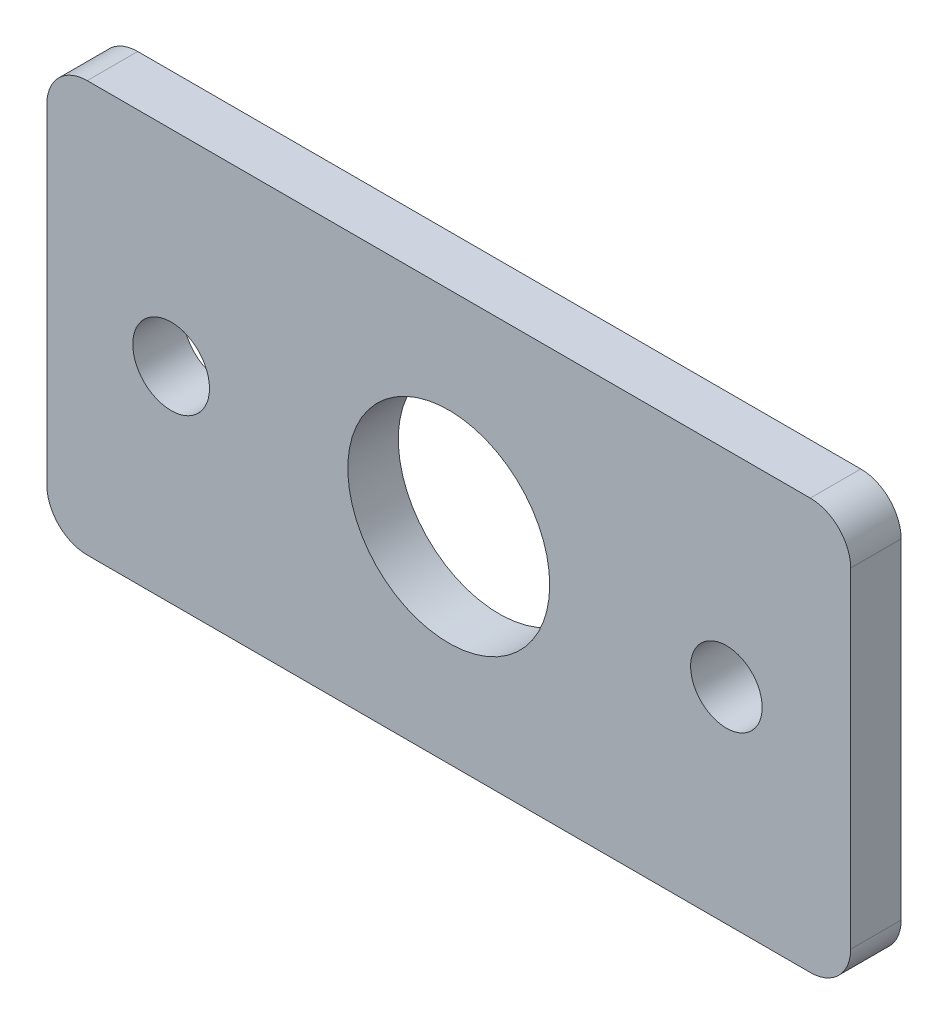
SolidWorks part; units mm, degrees
material "Plain Carbon Steel"
ref_plane "Front Plane" through (0, 0, 0) normal (0, 0, 1) x (1, 0, 0)
ref_plane "Top Plane" through (0, 0, 0) normal (0, 1, 0) x (1, 0, 0)
ref_plane "Right Plane" through (0, 0, 0) normal (1, 0, 0) x (0, 0, -1)
sketch "Sketch1" plane through (0, 0, 0) normal (0, 0, 1) x (1, 0, 0)
  line L1 (-25.2779, -12.9213) -> (25.2779, -12.9213)
  line L2 (-25.2779, -12.9213) -> (-25.2779, 12.9213)
  line L3 (-25.2779, 12.9213) -> (25.2779, 12.9213)
  line L4 (25.2779, -12.9213) -> (25.2779, 12.9213)
  line L5 (-25.2779, -12.9213) -> (25.2779, 12.9213) construction
  line L6 (-25.2779, 12.9213) -> (25.2779, -12.9213) construction
  circle A0 centre (-17.4625, 0) radius 2.413
  circle A1 centre (17.4625, 0) radius 2.2498
  circle A2 centre (0, 0) radius 6.35
extrude "Boss-Extrude1" add sketch "Sketch1" along normal blind 3.175
fillet "Fillet1" radius 2.54 4 edges at (-25.2779, -12.9213, 1.5875) (25.2779, -12.9213, 1.5875) (25.2779, 12.9213, 1.5875) (-25.2779, 12.9213, 1.5875)
